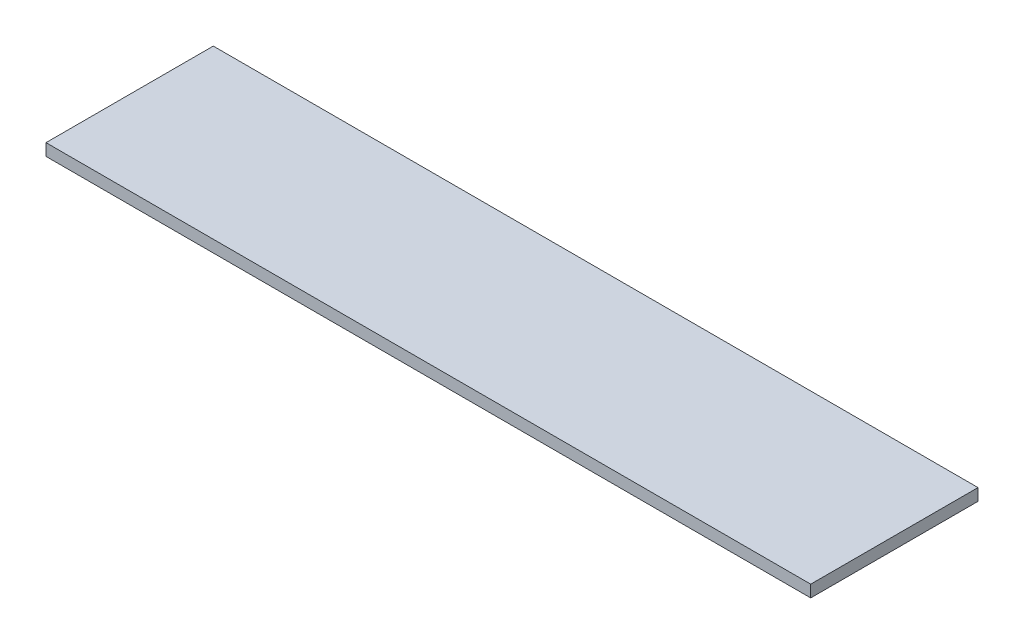
SolidWorks part; units mm, degrees
ref_plane "Front Plane" through (0, 0, 0) normal (0, 0, 1) x (1, 0, 0)
ref_plane "Top Plane" through (0, 0, 0) normal (0, 1, 0) x (1, 0, 0)
ref_plane "Right Plane" through (0, 0, 0) normal (1, 0, 0) x (0, 0, -1)
sketch "Sketch1" plane through (0, 0, 0) normal (0, 1, 0) x (1, 0, 0)
  line L1 (0, 0) -> (1219.2, 0)
  line L2 (0, 0) -> (0, 266.7)
  line L3 (0, 266.7) -> (1219.2, 266.7)
  line L4 (1219.2, 0) -> (1219.2, 266.7)
  dimension "D1" = 266.7
  dimension "D2" = 1219.2
extrude "Boss-Extrude1" add sketch "Sketch1" along normal blind 19.05
